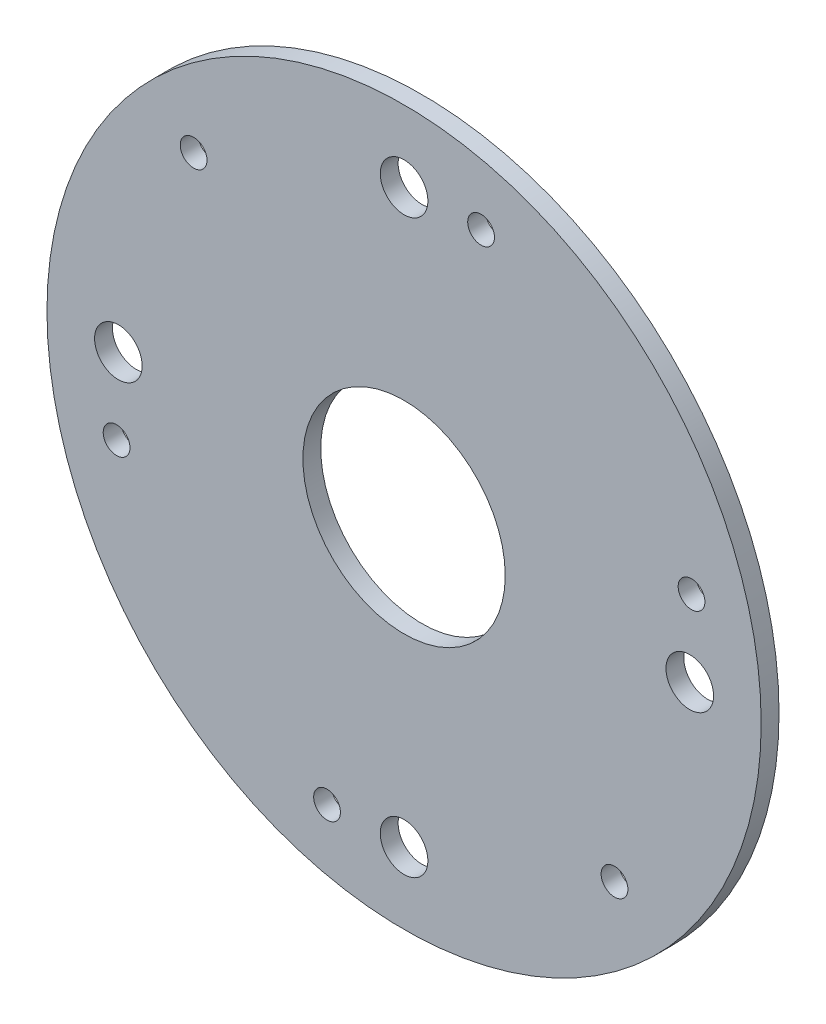
SolidWorks part; units mm, degrees
ref_plane "Спереди" through (0, 0, 0) normal (0, 0, 1) x (1, 0, 0)
ref_plane "Сверху" through (0, 0, 0) normal (0, 1, 0) x (1, 0, 0)
ref_plane "Справа" through (0, 0, 0) normal (1, 0, 0) x (0, 0, -1)
sketch "Эскиз1" plane through (0, 0, 0) normal (0, 0, 1) x (1, 0, 0)
  circle A0 centre (0, 0) radius 60
  circle A1 centre (0, 0) radius 17
extrude "Carrier_front" add sketch "Эскиз1" along normal blind 3 from offset 55.5
sketch "Эскиз2" plane through (0, 0, 0) normal (0, 0, 1) x (1, 0, 0)
  circle A0 centre (48, 0) radius 2.25
  circle A1 centre (0, 48) radius 2.25
  circle A2 centre (-48, 0) radius 2.25
  circle A3 centre (0, -48) radius 2.25
  circle A4 centre (48.2963, 12.941) radius 2.25
  circle A5 centre (12.941, 48.2963) radius 2.25
  circle A6 centre (-35.3553, 35.3553) radius 2.25
  circle A7 centre (-48.2963, -12.941) radius 2.25
  circle A8 centre (-12.941, -48.2963) radius 2.25
  circle A9 centre (35.3553, -35.3553) radius 2.25
extrude "Through_holes" cut sketch "Эскиз2" against normal mid plane 200
sketch "Эскиз3" plane through (0, 0, 0) normal (0, 0, 1) x (1, 0, 0)
  circle A0 centre (48, 0) radius 4
  circle A1 centre (0, 48) radius 4
  circle A2 centre (-48, 0) radius 4
  circle A3 centre (0, -48) radius 4
extrude "Вырез-Вытянуть2" cut sketch "Эскиз3" against normal mid plane 200
